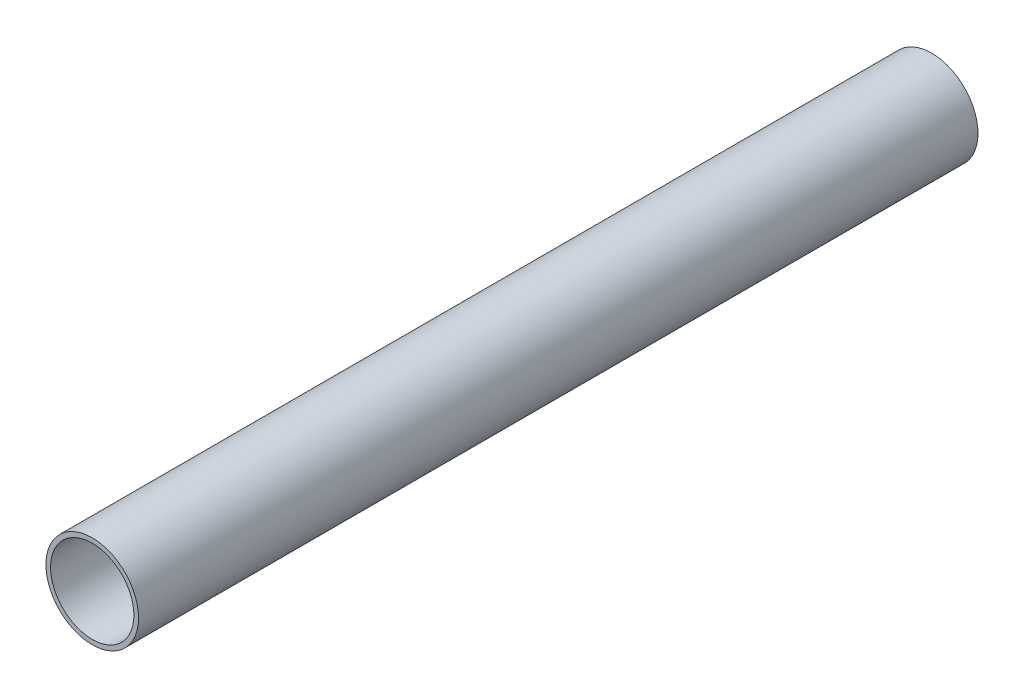
SolidWorks part; units mm, degrees
other "Defeature"
material "6061 Alloy"
ref_plane "Front Plane" through (0, 0, 0) normal (0, 0, 1) x (1, 0, 0)
ref_plane "Top Plane" through (0, 0, 0) normal (0, 1, 0) x (1, 0, 0)
ref_plane "Right Plane" through (0, 0, 0) normal (1, 0, 0) x (0, 0, -1)
sketch "Sketch1" plane through (0, 0, 0) normal (0, 0, 1) x (1, 0, 0)
  circle A0 centre (0, 0) radius 8
  circle A1 centre (0, 0) radius 7.2
  dimension "D1" = 16
  dimension "D2" = 0.8
extrude "Boss-Extrude1" add sketch "Sketch1" along normal mid plane 145
